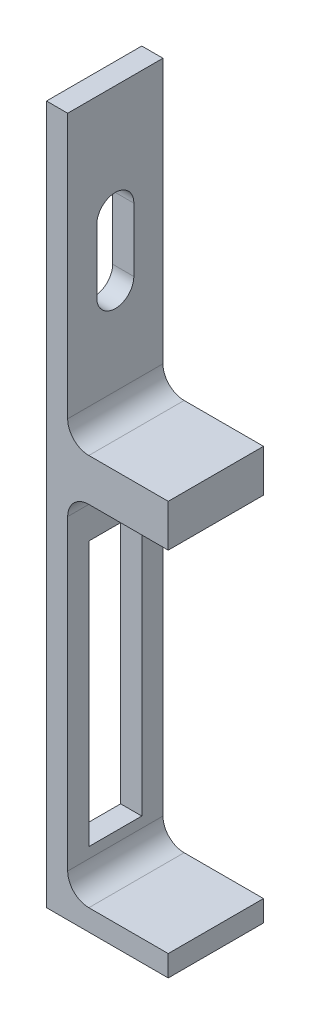
SolidWorks part; units mm, degrees
material "ПВХ Жесткий"
ref_plane "Спереди" through (0, 0, 0) normal (0, 0, 1) x (1, 0, 0)
ref_plane "Сверху" through (0, 0, 0) normal (0, 1, 0) x (1, 0, 0)
ref_plane "Справа" through (0, 0, 0) normal (1, 0, 0) x (0, 0, -1)
sketch "Эскиз1" plane through (0, 0, 0) normal (0, 0, 1) x (1, 0, 0)
  line L0 (0, 0) -> (11.5, 0)
  line L1 (11.5, 0) -> (11.5, 2)
  line L2 (11.5, 2) -> (2, 2)
  line L3 (2, 2) -> (2, 66)
  line L4 (2, 66) -> (0, 66)
  line L5 (0, 66) -> (0, 0)
  dimension "D1" = 2
  dimension "D2" = 66
  dimension "D3" = 11.5
extrude "Бобышка-Вытянуть1" add sketch "Эскиз1" along normal blind 9
sketch "Эскиз2" plane through (2, 0, 0) normal (1, 0, 0) x (0, 0, -1)
  line L0 (-4.5, 66) -> (-4.5, 2) construction
  line L1 (-9, 66) -> (0, 66) construction
  line L2 (-9, 2) -> (0, 2) construction
ref_plane "Плоскость1" through (0, 0, 4.5) normal (0, 0, 1) x (0, -1, 0)
sketch "Эскиз3" plane through (0, 0, 0) normal (-1, 0, 0) x (0, 0, 1)
  line L0 (9, 66) -> (0, 66) construction
  line L1 (4.5, 66) -> (4.5, 2) construction
  line L2 (4.5, 66) -> (4.5, 2) construction
  circle A1 centre (4.5, 52.52) radius 1.75
  dimension "D1" = 13.48
  dimension "D2" = 3.5
sketch "Эскиз4" plane through (0, 0, 0) normal (-1, 0, 0) x (0, 0, 1)
  line L0 (4.5, 55.52) -> (4.5, 49.52) construction
  line L1 (6.25, 55.52) -> (6.25, 49.52)
  line L2 (2.75, 55.52) -> (2.75, 49.52)
  line L3 (4.5, 66) -> (4.5, 43.3234) construction
  line L4 (9, 66) -> (0, 66) construction
  circle A0 centre (4.5, 52.52) radius 1.75 construction
  circle A1 centre (4.5, 52.52) radius 1.75 construction
  arc A2 (6.25, 55.52) -> (2.75, 55.52) centre (4.5, 55.52) ccw
  arc A3 (2.75, 49.52) -> (6.25, 49.52) centre (4.5, 49.52) ccw
  point P5 (4.5, 52.52)
  dimension "D1" = 6
extrude "Вырез-Вытянуть2" cut sketch "Эскиз4" against normal through all
sketch "Эскиз5" plane through (0, 0, 9) normal (0, 0, 1) x (1, 0, 0)
  line L0 (2, 2) -> (2, 66) construction
  line L1 (11.5, 2) -> (2, 2) construction
  line L2 (2, 2) -> (2, 9)
  line L3 (11.5, 2) -> (2, 2)
  line L4 (11.5, 2) -> (2, 9)
  dimension "D1" = 7
sketch "Эскиз6" plane through (2, 0, 0) normal (1, 0, 0) x (0, 0, -1)
  line L0 (-7, 5) -> (-2, 5)
  line L1 (-7, 5) -> (-7, 30)
  line L2 (-2, 5) -> (-2, 30)
  line L3 (-7, 30) -> (-2, 30)
  line L4 (-4.5, 30) -> (-4.5, 5) construction
  line L5 (-4.5, 66) -> (-4.5, 2) construction
  line L6 (-9, 2) -> (-9, 66) construction
  line L7 (-9, 2) -> (0, 2) construction
  dimension "D1" = 2
  dimension "D2" = 3
  dimension "D3" = 25
extrude "Вырез-Вытянуть3" cut sketch "Эскиз6" against normal through all
fillet "Скругление1" radius 2 1 edges at (2, 2, 4.5)
sketch "Эскиз7" plane through (0, 0, 9) normal (0, 0, 1) x (1, 0, 0)
  line L0 (2, 39) -> (2, 35)
  line L1 (2, 39) -> (11.5, 39)
  line L2 (2, 35) -> (11.5, 35)
  line L3 (11.5, 39) -> (11.5, 35)
  line L4 (2, 4) -> (2, 66) construction
  line L5 (0, 0) -> (11.5, 0) construction
  line L6 (11.5, 0) -> (11.5, 2) construction
  dimension "D1" = 35
  dimension "D2" = 4
extrude "Бобышка-Вытянуть2" add sketch "Эскиз7" against normal up to surface (9 mm away) up to face at (4.3694, 19.9408, 0)
fillet "Скругление2" radius 2 2 edges at (2, 39, 4.5) (2, 35, 4.5)
